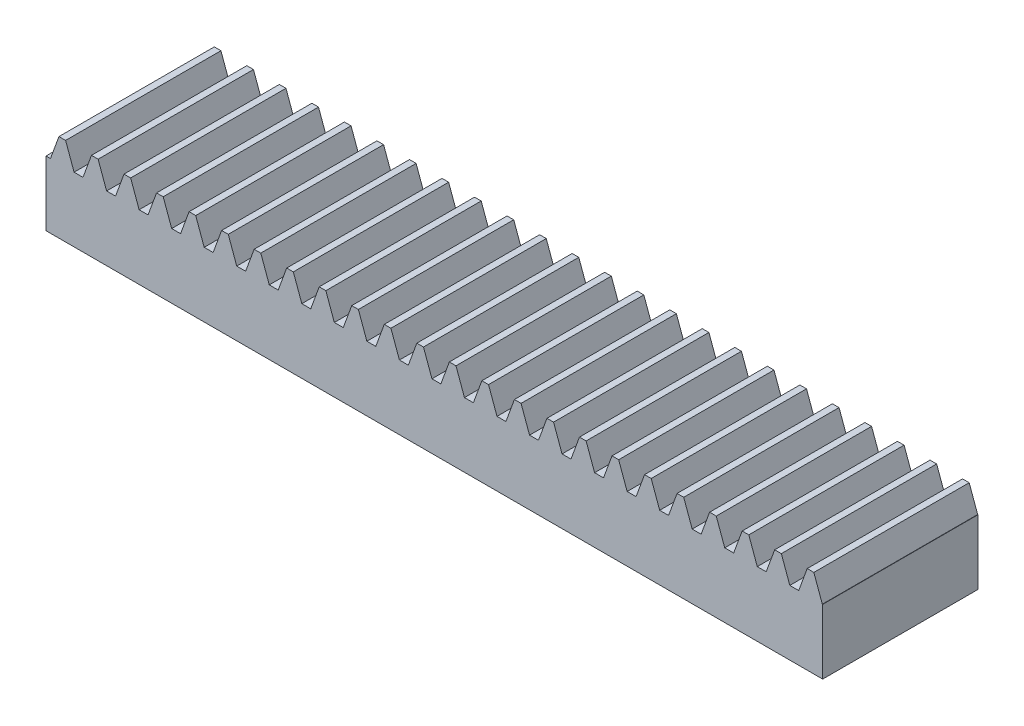
SolidWorks part; units mm, degrees
extrude "Blank" add sketch "BlankSke" against normal blind 30
sketch "BlankSke" plane through (0, 0, 0) normal (0, 0, 1) x (1, 0, 0)
  line L1 (0, 0) -> (150, 0)
  line L2 (0, 0) -> (0, 17)
  line L3 (0, 17) -> (150, 17)
  line L4 (150, 0) -> (150, 17)
  dimension "Length" = 150
  dimension "Blank_height" = 17
ref_plane "Plane1" through (0, 0, 0) normal (0, 0, 1) x (1, 0, 0)
ref_plane "Plane2" through (0, 0, 0) normal (0, 1, 0) x (1, 0, 0)
ref_plane "Plane3" through (0, 0, 0) normal (1, 0, 0) x (0, 0, -1)
other "Configuration Table"
sketch "HoldingSke" plane through (0, 0, 0) normal (0, 1, 0) x (1, 0, 0)
  line L0 (0, 0) -> (0.0696, 0.4951)
  line L1 (-15, 0) -> (100, 0) construction
  line L2 (0, 0) -> (-2.1039, 2.3779)
  line L3 (0, 0) -> (-11.863, 4.5341)
  line L4 (0, 0) -> (7.8269, 3.6497)
  line L5 (0, 0) -> (-23.7986, -8.8762)
  line L6 (0, 0) -> (-10.5278, -7.1032)
  line L9 (-71.009, 38.7566) -> (69.9449, 90.0596)
  line L10 (-76.2, 4.3779) -> (-61.2, 4.3779)
  line L11 (0, 0) -> (-30, 0)
  line L12 (-76.2, 101.6) -> (-76.133, 101.6)
  line L13 (24.9733, 27.94) -> (52.9518, 28.4284)
  line L14 (24.9733, 27.94) -> (24.9743, 27.94)
  line L15 (24.9733, 27.94) -> (100.4006, 29.5858)
  circle A0 centre (0, 0) radius 19.05
  circle A1 centre (0, 0) radius 7.5
  circle A2 centre (0, 0) radius 12.7
  dimension "MPH" = 15
  dimension "Diameter" = 38.1
  dimension "Num_teeth" = 25
  dimension "Pitch" = 0.5
  dimension "Show_teeth" = 998
  dimension "Thickness" = 12.7
  dimension "Ap" = 20
  dimension "Pitch_height" = 15
  dimension "Width" = 30
  dimension "Backlash" = 0.067
  dimension "Addendum_fac" = 1
  dimension "Dedendum_fac" = 1.25
  dimension "Clearance_fac" = 0.25
  dimension "Dedendum_add" = 0.001
  dimension "Length" = 150
  dimension "Module" = 2
sketch "TooCutSkeIll" plane through (0, 0, 0) normal (0, 0, 1) x (1, 0, 0)
  line L0 (-2.4806, 16.9474) -> (-0.9819, 12.8296)
  line L1 (-0.5111, 12.5) -> (0.5111, 12.5)
  line L2 (0.9819, 12.8296) -> (2.4806, 16.9474)
  line L3 (150, 17) -> (0, 17) construction
  line L4 (0, 0) -> (0, 64.897) construction
  line L5 (-13.208, 15) -> (12.954, 15) construction
  line L6 (0, 0) -> (150, 0) construction
  line L7 (1.7718, 15) -> (1.7718, 48.7463) construction
  line L8 (-1.7718, 15) -> (-1.7718, 48.7463) construction
  line L9 (2.5558, 17) -> (2.5558, 17.0254)
  line L10 (-2.5558, 17) -> (-2.5558, 17.0254)
  line L11 (-2.5558, 17.0254) -> (2.5558, 17.0254)
  arc A0 (0.5111, 12.5) -> (0.9819, 12.8296) centre (0.5111, 13.001) ccw
  arc A1 (-0.9819, 12.8296) -> (-0.5111, 12.5) centre (-0.5111, 13.001) ccw
  arc A2 (2.5558, 17) -> (2.4806, 16.9474) centre (2.5558, 16.92) ccw
  arc A3 (-2.4806, 16.9474) -> (-2.5558, 17) centre (-2.5558, 16.92) ccw
  dimension "Pitch_height" = 15
  dimension "Addendum_plus" = 2.0254
  dimension "Pressure_angle" = 20
  dimension "Gap_width" = 3.5436
  dimension "Dedendum" = 2.5
extrude "ToothCutIll" [suppressed] cut sketch "TooCutSkeIll" against normal through all
sketch "TooCutSkeSim" plane through (0, 0, 0) normal (0, 0, 1) x (1, 0, 0)
  line L0 (0.8619, 12.5) -> (-0.8619, 12.5)
  line L1 (2.509, 17.0254) -> (0.8619, 12.5)
  line L2 (0, 17.4625) -> (0, 53.467) construction
  line L3 (2.509, 17.0254) -> (-2.509, 17.0254)
  line L6 (-2.509, 17.0254) -> (-0.8619, 12.5)
  line L9 (-1.7718, 15) -> (1.7718, 15) construction
  line L10 (0, 0) -> (150, 0) construction
  line L11 (1.7718, 15) -> (1.7718, 53.467) construction
  line L12 (-1.7718, 15) -> (-1.7718, 53.467) construction
  dimension "Pitch_height" = 15
  dimension "Addendum_plus" = 2.0254
  dimension "Pressure_angle" = 20
  dimension "Gap_width" = 3.5436
  dimension "Dedendum" = 2.5
extrude "ToothCutSim" cut sketch "TooCutSkeSim" against normal through all
pattern_linear "TeethCuts" count 25 spacing 6.2832 along (1, 0, 0) of "ToothCutIll", "ToothCutSim"
equation "' \"Module@HoldingSke\" = 6.35"
equation "' \"Num_teeth@HoldingSke\" = 12"
equation "' \"Ap@HoldingSke\" =  20"
equation "' \"Ap@HoldingSke\" = 20"
equation "' \"Width@HoldingSke\" = 0.25 * 25.4"
equation "' \"Show_teeth@HoldingSke\" = 500"
equation "' \"Backlash@HoldingSke\" = 0.009 * 25.4"
equation "' \"Addendum_fac@HoldingSke\" = 1.0"
equation "' \"Dedendum_fac@HoldingSke\" = 1.25"
equation "' \"Dedendum_add@HoldingSke\" = 0.00005 * 25.4"
equation "' \"Clearance_fac@HoldingSke\" = 0.25"
equation "' \"Pitch_height@HoldingSke\" = 1 * 25.4"
equation "' \"Length@HoldingSke\" = 4.71 * 25.4"
equation "\"Pitch@HoldingSke\" = 1 / \"Module@HoldingSke\""
equation "\"MPH@HoldingSke\" = \"Dedendum_fac@HoldingSke\" / \"Pitch@HoldingSke\" + 2 * \"Dedendum_add@HoldingSke\" + 0.002 * 25.4"
equation "\"MPH@HoldingSke\" = ((sgn( \"MPH@HoldingSke\" - \"Pitch_height@HoldingSke\")+1)*( \"MPH@HoldingSke\" - \"Pitch_height@HoldingSke\"))/2 + \"Pitch_height@HoldingSke\""
equation "\"Blank_height@BlankSke\" = \"Pitch_height@HoldingSke\" + \"Addendum_fac@HoldingSke\"  / \"Pitch@HoldingSke\" "
equation "\"Length@BlankSke\" =  \"Length@HoldingSke\""
equation "\"Face_width@Blank\" = \"Width@HoldingSke\""
equation "\"Pressure_angle@TooCutSkeIll\" = \"Ap@HoldingSke\""
equation "\"Addendum_plus@TooCutSkeIll\" =  \"Addendum_fac@HoldingSke\"  / \"Pitch@HoldingSke\" + 0.001 *25.4"
equation "\"Dedendum@TooCutSkeIll\" = \"Dedendum_fac@HoldingSke\"  / \"Pitch@HoldingSke\""
equation "\"Pitch_height@TooCutSkeIll\" =  \"MPH@HoldingSke\""
equation "\"Gap_width@TooCutSkeIll\" = 3.14159265 / 2 / \"Pitch@HoldingSke\" + 6 * \"Backlash@HoldingSke\""
equation "\"Pressure_angle@TooCutSkeSim\" = \"Ap@HoldingSke\""
equation "\"Addendum_plus@TooCutSkeSim\" =  \"Addendum_fac@HoldingSke\"  / \"Pitch@HoldingSke\" + 0.001 * 25.4"
equation "\"Dedendum@TooCutSkeSim\" = \"Dedendum_fac@HoldingSke\"  / \"Pitch@HoldingSke\""
equation "\"Pitch_height@TooCutSkeSim\" =  \"MPH@HoldingSke\""
equation "\"Gap_width@TooCutSkeSim\" = 3.14159265 / 2 / \"Pitch@HoldingSke\" + 6 * \"Backlash@HoldingSke\""
equation "\"Root_fillet@TooCutSkeIll\" = \"Clearance_fac@HoldingSke\" / \"Pitch@HoldingSke\" + \"Dedendum_add@HoldingSke\""
equation "\"Break_rad@TooCutSkeIll\" = 0.02 / \"Pitch@HoldingSke\" * 2"
equation "\"Linear_pitch@TeethCuts\" = 3.14159265 / \"Pitch@HoldingSke\""
equation "\"Num_teeth@HoldingSke\" = int( ( \"Length@HoldingSke\" + 0 ) / (3.14159265 / \"Pitch@HoldingSke\")) + 0.9999  + 1"
equation " \"Num_teeth@TeethCuts\" = int( \"Show_teeth@HoldingSke\" ) + 1"
equation " \"Num_teeth@TeethCuts\" = ((sgn( \"Num_teeth@TeethCuts\" - \"Num_teeth@HoldingSke\" )-1)*( \"Num_teeth@TeethCuts\" - \"Num_teeth@HoldingSke\" ))/-2+ \"Num_teeth@HoldingSke\""
equation " \"Num_teeth@TeethCuts\" = ((sgn( \"Num_teeth@TeethCuts\" - 2.0)+1)*( \"Num_teeth@TeethCuts\" - 2.0))/2 +2.0"
